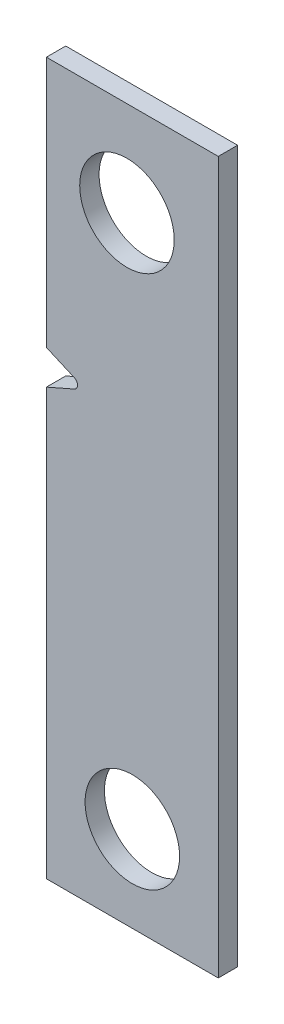
SolidWorks part; units mm, degrees
ref_plane "Front Plane" through (0, 0, 0) normal (0, 0, 1) x (1, 0, 0)
ref_plane "Top Plane" through (0, 0, 0) normal (0, 1, 0) x (1, 0, 0)
ref_plane "Right Plane" through (0, 0, 0) normal (1, 0, 0) x (0, 0, -1)
sketch "Sketch1" plane through (0, 0, 0) normal (0, 0, 1) x (1, 0, 0)
  line L1 (-21.25, 20) -> (21.25, 20)
  line L2 (-21.25, 20) -> (-21.25, -20)
  line L3 (-21.25, -20) -> (21.25, -20)
  line L4 (21.25, 20) -> (21.25, -20)
  line L5 (-21.25, 20) -> (21.25, -20) construction
  line L6 (-21.25, -20) -> (21.25, 20) construction
  point P0 (0, 0)
  dimension "D1" = 42.5
  dimension "D2" = 40
extrude "Boss-Extrude1" add sketch "Sketch1" along normal mid plane 4.5
sketch "Sketch3" plane through (0, 0, 2.25) normal (0, 0, 1) x (1, 0, 0)
  line L0 (21.25, -20) -> (21.25, 20) construction
  line L1 (-21.25, -20) -> (21.25, -20) construction
  circle A7 centre (1.25, 0) radius 11
  dimension "D2" = 20
  dimension "D1" = 20
  dimension "D3" = 22
extrude "Cut-Extrude2" cut sketch "Sketch3" against normal mid plane 10
sketch "Sketch4" plane through (0, 20, 0) normal (0, 1, 0) x (1, 0, 0)
  line L1 (-21.25, 2.25) -> (21.25, 2.25)
  line L2 (-21.25, 2.25) -> (-21.25, -2.25)
  line L3 (-21.25, -2.25) -> (21.25, -2.25)
  line L4 (21.25, 2.25) -> (21.25, -2.25)
extrude "Boss-Extrude2" add sketch "Sketch4" along normal blind 15
sketch "Sketch8" plane through (0, 0, 2.25) normal (0, 0, 1) x (1, 0, 0)
  line L0 (-21.25, -20) -> (21.25, -20) construction
  line L1 (-18.75, -20) -> (-21.25, -20)
  line L2 (-18.75, -20) -> (-18.75, 35)
  line L3 (-18.75, 35) -> (-21.25, 35)
  line L4 (-21.25, -20) -> (-21.25, 35)
  dimension "D1" = 2.5
extrude "Cut-Extrude4" cut sketch "Sketch8" against normal blind 10
sketch "Sketch9" plane through (0, 35, 0) normal (0, 1, 0) x (1, 0, 0)
  line L1 (-18.75, 2.25) -> (21.25, 2.25)
  line L2 (-18.75, 2.25) -> (-18.75, -2.25)
  line L3 (-18.75, -2.25) -> (21.25, -2.25)
  line L4 (21.25, 2.25) -> (21.25, -2.25)
extrude "Boss-Extrude3" add sketch "Sketch9" along normal up to surface (110.5999 mm away)
sketch "Sketch11" plane through (0, 0, -2.25) normal (0, 0, -1) x (-1, 0, 0)
  line L0 (-21.25, 145.5999) -> (18.75, 145.5999) construction
  circle A0 centre (0, 123.5999) radius 11
  dimension "D1" = 22
  dimension "D2" = 22
extrude "Cut-Extrude5" cut sketch "Sketch11" against normal blind 100
sketch "Sketch12" plane through (0, 0, -2.25) normal (0, 0, -1) x (-1, 0, 0)
  line L0 (-21.25, 145.5999) -> (18.75, 145.5999) construction
  line L1 (9.6411, 83.0999) -> (18.75, 79.0999)
  line L2 (18.75, -20) -> (18.75, 145.5999) construction
  line L3 (18.75, 87.0999) -> (9.6411, 83.0999)
  line L4 (12.75, 83.0999) -> (18.75, 83.0999) construction
  circle A0 centre (12.75, 83.0999) radius 1.25
  point P10 (0, 0)
  point P12 (6.9638, 83.0999)
  dimension "D2" = 2.5
  dimension "D1" = 62.5
  dimension "D3" = 6
  dimension "D4" = 4
extrude "Cut-Extrude6" cut sketch "Sketch12" against normal blind 100
